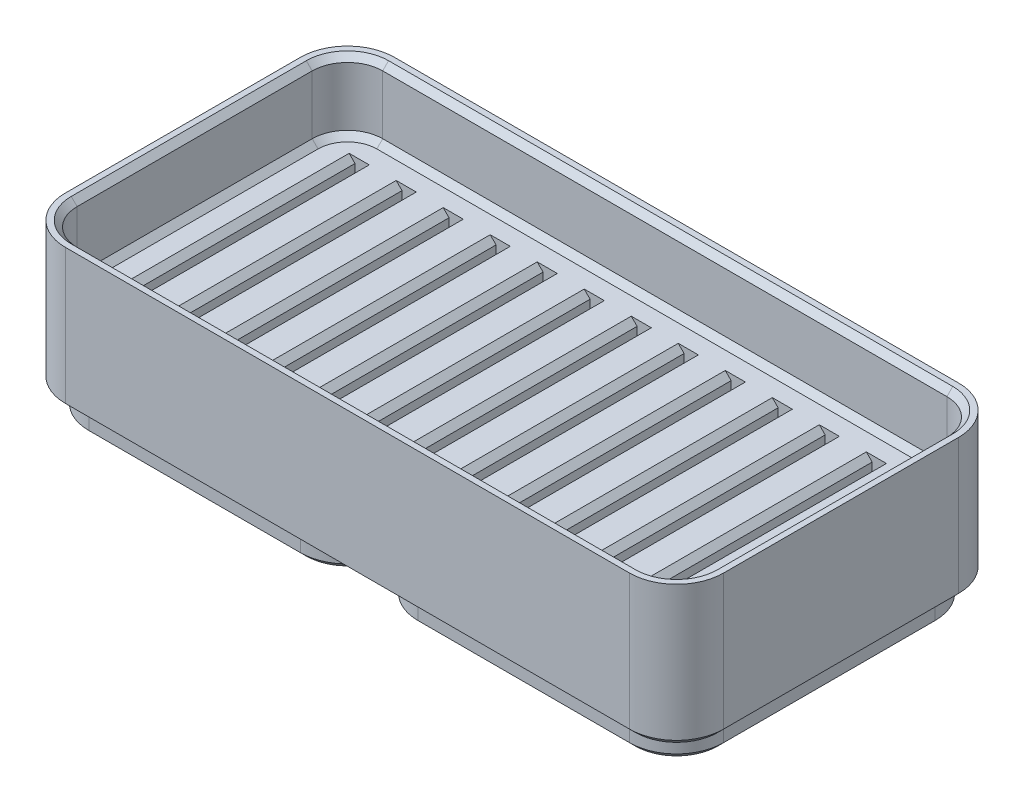
SolidWorks part; units mm, degrees
ref_plane "Front Plane" through (0, 0, 0) normal (0, 0, 1) x (1, 0, 0)
ref_plane "Top Plane" through (0, 0, 0) normal (0, 1, 0) x (1, 0, 0)
ref_plane "Right Plane" through (0, 0, 0) normal (1, 0, 0) x (0, 0, -1)
sketch "Sketch5" plane through (0, 0, 0) normal (0, 1, 0) x (1, 0, 0)
  line L1 (-22.5, -32.5) -> (22.5, -32.5)
  line L2 (-32.5, -22.5) -> (-32.5, 22.5)
  line L3 (-22.5, 32.5) -> (22.5, 32.5)
  line L4 (32.5, -22.5) -> (32.5, 22.5)
  line L5 (-32.5, -32.5) -> (32.5, 32.5) construction
  line L6 (-32.5, 32.5) -> (32.5, -32.5) construction
  arc A0 (-22.5, -32.5) -> (-32.5, -22.5) centre (-22.5, -22.5) cw
  arc A1 (22.5, -32.5) -> (32.5, -22.5) centre (22.5, -22.5) ccw
  arc A2 (22.5, 32.5) -> (32.5, 22.5) centre (22.5, 22.5) cw
  arc A3 (-32.5, 22.5) -> (-22.5, 32.5) centre (-22.5, 22.5) cw
  point P0 (0, 0)
  dimension "D3" = 10
  dimension "D1" = 65
  dimension "D2" = 65
extrude "Boss-Extrude4" add sketch "Sketch5" along normal blind 5
sketch "Sketch6" plane through (0, 5, 0) normal (0, 1, 0) x (1, 0, 0)
  line L1 (35, 35) -> (-35, 35)
  line L2 (35, 35) -> (35, -35)
  line L3 (35, -35) -> (-35, -35)
  line L4 (-35, 35) -> (-35, -35)
  line L5 (35, 35) -> (-35, -35) construction
  line L6 (35, -35) -> (-35, 35) construction
  point P0 (0, 0)
extrude "Boss-Extrude5" add sketch "Sketch6" along normal blind 30
sketch "Sketch8" plane through (0, 0, 0) normal (0, -1, 0) x (1, 0, 0)
  line L0 (-29.5711, 29.5711) -> (-22.5, 22.5)
  arc A0 (-22.5, 32.5) -> (-32.5, 22.5) centre (-22.5, 22.5) ccw construction
  circle A1 centre (-26.0355, 26.0355) radius 3
  circle A2 centre (26.0365, 26.0365) radius 3
  circle A3 centre (26.0375, -26.0355) radius 3
  circle A4 centre (-26.0345, -26.0365) radius 3
  point P8 (0, 0)
  point P15 (0.001, 0.001)
  point P18 (0.002, 0)
  point P21 (0.001, -0.001)
  point P22 (0.001, 0)
  dimension "D1" = 4
extrude "Cut-Extrude1" cut sketch "Sketch8" against normal blind 2 contours A3 | A2 | L0 A1 | L0 A1 | A4
mirror "Mirror1" about plane through (-35, 35, -35) normal (1, 0, 0) of bodies 112
sketch "Sketch9" plane through (0, 35, 0) normal (0, 1, 0) x (1, 0, 0)
  line L8 (32.5, 32.5) -> (-102.5, 32.5)
  line L9 (-102.5, 32.5) -> (-102.5, -32.5)
  line L10 (-102.5, -32.5) -> (32.5, -32.5)
  line L11 (32.5, -32.5) -> (32.5, 32.5)
  line L12 (22.5, 32.5) -> (-92.5, 32.5)
  line L13 (-102.5, 22.5) -> (-102.5, -22.5)
  line L14 (-92.5, -32.5) -> (22.5, -32.5)
  line L15 (32.5, -22.5) -> (32.5, 22.5)
  arc A0 (-102.5, -22.5) -> (-92.5, -32.5) centre (-92.5, -22.5) ccw
  arc A1 (22.5, -32.5) -> (32.5, -22.5) centre (22.5, -22.5) ccw
  arc A2 (22.5, 32.5) -> (32.5, 22.5) centre (22.5, 22.5) cw
  arc A3 (-92.5, 32.5) -> (-102.5, 22.5) centre (-92.5, 22.5) ccw
  dimension "D2" = 10
  dimension "D1" = 2.5
extrude "Cut-Extrude2" cut sketch "Sketch9" against normal blind 30
sketch "Sketch10" plane through (0, 5, 0) normal (0, -1, 0) x (1, 0, 0)
  line L8 (35, 35) -> (-105, 35)
  line L9 (-105, 35) -> (-105, -35)
  line L10 (-105, -35) -> (35, -35)
  line L11 (35, -35) -> (35, 35)
  line L12 (35, 35) -> (-105, 35)
  line L13 (-105, 35) -> (-105, -35)
  line L14 (-105, -35) -> (35, -35)
  line L15 (35, -35) -> (35, 35)
  dimension "D1" = 0
extrude "Boss-Extrude6" add sketch "Sketch10" against normal blind 2.5
fillet "Fillet1" radius 10 4 edges at (35, 20, -35) (35, 20, 35) (-105, 20, 35) (-105, 20, -35)
sketch "Sketch11" plane through (0, 35, 0) normal (0, 1, 0) x (1, 0, 0)
  line L0 (22.5, 32.5) -> (-92.5, 32.5) construction
  line L1 (-136.2871, 123.1679) -> (66.2871, 123.1679)
  line L2 (-136.2871, 123.1679) -> (-136.2871, -58.1679)
  line L3 (-136.2871, -58.1679) -> (66.2871, -58.1679)
  line L4 (66.2871, 123.1679) -> (66.2871, -58.1679)
  line L5 (-136.2871, 123.1679) -> (66.2871, -58.1679) construction
  line L6 (-136.2871, -58.1679) -> (66.2871, 123.1679) construction
  point P0 (-35, 32.5)
extrude "Cut-Extrude3" cut sketch "Sketch11" against normal blind 27.5
sketch "Sketch12" plane through (0, 7.5, 0) normal (0, 1, 0) x (1, 0, 0)
  line L4 (-85.8875, -27.5) -> (-85.8875, 27.5)
  line L5 (-85.8875, -27.5) -> (-84.1125, -27.5)
  line L6 (-84.1125, -27.5) -> (-84.1125, 27.5)
  line L7 (-85.8875, 27.5) -> (-84.1125, 27.5)
  line L12 (-75.8875, -27.5) -> (-75.8875, 27.5)
  line L13 (-75.8875, -27.5) -> (-74.1125, -27.5)
  line L14 (-74.1125, -27.5) -> (-74.1125, 27.5)
  line L15 (-75.8875, 27.5) -> (-74.1125, 27.5)
  line L20 (-65.8875, -27.5) -> (-65.8875, 27.5)
  line L21 (-65.8875, -27.5) -> (-64.1125, -27.5)
  line L22 (-64.1125, -27.5) -> (-64.1125, 27.5)
  line L23 (-65.8875, 27.5) -> (-64.1125, 27.5)
  line L28 (-55.8875, -27.5) -> (-55.8875, 27.5)
  line L29 (-55.8875, -27.5) -> (-54.1125, -27.5)
  line L30 (-54.1125, -27.5) -> (-54.1125, 27.5)
  line L31 (-55.8875, 27.5) -> (-54.1125, 27.5)
  line L36 (-45.8875, -27.5) -> (-45.8875, 27.5)
  line L37 (-45.8875, -27.5) -> (-44.1125, -27.5)
  line L38 (-44.1125, -27.5) -> (-44.1125, 27.5)
  line L39 (-45.8875, 27.5) -> (-44.1125, 27.5)
  line L44 (-35.8875, -27.5) -> (-35.8875, 27.5)
  line L59 (0, 0) -> (-7.2841, 0) construction
  line L60 (-95.8875, -27.5) -> (-94.1125, -27.5)
  line L61 (-95.8875, -27.5) -> (-95.8875, 27.5)
  line L62 (-95.8875, 27.5) -> (-94.1125, 27.5)
  line L63 (-94.1125, -27.5) -> (-94.1125, 27.5)
  line L64 (-95.8875, -27.5) -> (-94.1125, 27.5) construction
  line L65 (-95.8875, 27.5) -> (-94.1125, -27.5) construction
  line L66 (-35.8875, -27.5) -> (-34.1125, -27.5)
  line L67 (-34.1125, -27.5) -> (-34.1125, 27.5)
  line L68 (-35.8875, 27.5) -> (-34.1125, 27.5)
  line L73 (-25.8875, -27.5) -> (-25.8875, 27.5)
  line L74 (-25.8875, -27.5) -> (-24.1125, -27.5)
  line L75 (-24.1125, -27.5) -> (-24.1125, 27.5)
  line L76 (-25.8875, 27.5) -> (-24.1125, 27.5)
  line L81 (-15.8875, -27.5) -> (-15.8875, 27.5)
  line L82 (-15.8875, -27.5) -> (-14.1125, -27.5)
  line L83 (-14.1125, -27.5) -> (-14.1125, 27.5)
  line L84 (-15.8875, 27.5) -> (-14.1125, 27.5)
  line L89 (-5.8875, -27.5) -> (-5.8875, 27.5)
  line L90 (-5.8875, -27.5) -> (-4.1125, -27.5)
  line L91 (-4.1125, -27.5) -> (-4.1125, 27.5)
  line L92 (-5.8875, 27.5) -> (-4.1125, 27.5)
  line L97 (4.1125, -27.5) -> (4.1125, 27.5)
  line L98 (4.1125, -27.5) -> (5.8875, -27.5)
  line L99 (5.8875, -27.5) -> (5.8875, 27.5)
  line L100 (4.1125, 27.5) -> (5.8875, 27.5)
  line L105 (14.1125, -27.5) -> (14.1125, 27.5)
  line L106 (14.1125, -27.5) -> (15.8875, -27.5)
  line L107 (15.8875, -27.5) -> (15.8875, 27.5)
  line L108 (14.1125, 27.5) -> (15.8875, 27.5)
  line L113 (24.1125, -27.5) -> (24.1125, 27.5)
  line L114 (24.1125, -27.5) -> (25.8875, -27.5)
  line L115 (25.8875, -27.5) -> (25.8875, 27.5)
  line L116 (24.1125, 27.5) -> (25.8875, 27.5)
  line L137 (-105, 25) -> (-105, -25)
  line L138 (-95, -35) -> (25, -35)
  line L139 (35, -25) -> (35, 25)
  line L140 (25, 35) -> (-95, 35)
  line L141 (-105, 25) -> (-105, -25)
  line L142 (-95, -35) -> (25, -35)
  line L143 (35, -25) -> (35, 25)
  line L144 (25, 35) -> (-95, 35)
  line L145 (-90.8875, -27.5) -> (-90.8875, 27.5) [skipped]
  line L146 (-90.8875, 27.5) -> (-89.1125, 27.5) [skipped]
  line L147 (-89.1125, -27.5) -> (-89.1125, 27.5) [skipped]
  line L148 (-90.8875, -27.5) -> (-89.1125, -27.5) [skipped]
  line L149 (-80.8875, -27.5) -> (-80.8875, 27.5) [skipped]
  line L150 (-80.8875, 27.5) -> (-79.1125, 27.5) [skipped]
  line L151 (-79.1125, -27.5) -> (-79.1125, 27.5) [skipped]
  line L152 (-80.8875, -27.5) -> (-79.1125, -27.5) [skipped]
  line L153 (-70.8875, -27.5) -> (-70.8875, 27.5) [skipped]
  line L154 (-70.8875, 27.5) -> (-69.1125, 27.5) [skipped]
  line L155 (-69.1125, -27.5) -> (-69.1125, 27.5) [skipped]
  line L156 (-70.8875, -27.5) -> (-69.1125, -27.5) [skipped]
  line L157 (-60.8875, -27.5) -> (-60.8875, 27.5) [skipped]
  line L158 (-60.8875, 27.5) -> (-59.1125, 27.5) [skipped]
  line L159 (-59.1125, -27.5) -> (-59.1125, 27.5) [skipped]
  line L160 (-60.8875, -27.5) -> (-59.1125, -27.5) [skipped]
  line L161 (-50.8875, -27.5) -> (-50.8875, 27.5) [skipped]
  line L162 (-50.8875, 27.5) -> (-49.1125, 27.5) [skipped]
  line L163 (-49.1125, -27.5) -> (-49.1125, 27.5) [skipped]
  line L164 (-50.8875, -27.5) -> (-49.1125, -27.5) [skipped]
  line L165 (-40.8875, -27.5) -> (-40.8875, 27.5) [skipped]
  line L166 (-40.8875, 27.5) -> (-39.1125, 27.5) [skipped]
  line L167 (-39.1125, -27.5) -> (-39.1125, 27.5) [skipped]
  line L168 (-40.8875, -27.5) -> (-39.1125, -27.5) [skipped]
  line L169 (-30.8875, -27.5) -> (-30.8875, 27.5) [skipped]
  line L170 (-30.8875, 27.5) -> (-29.1125, 27.5) [skipped]
  line L171 (-29.1125, -27.5) -> (-29.1125, 27.5) [skipped]
  line L172 (-30.8875, -27.5) -> (-29.1125, -27.5) [skipped]
  line L173 (-20.8875, -27.5) -> (-20.8875, 27.5) [skipped]
  line L174 (-20.8875, 27.5) -> (-19.1125, 27.5) [skipped]
  line L175 (-19.1125, -27.5) -> (-19.1125, 27.5) [skipped]
  line L176 (-20.8875, -27.5) -> (-19.1125, -27.5) [skipped]
  line L177 (-10.8875, -27.5) -> (-10.8875, 27.5) [skipped]
  line L178 (-10.8875, 27.5) -> (-9.1125, 27.5) [skipped]
  line L179 (-9.1125, -27.5) -> (-9.1125, 27.5) [skipped]
  line L180 (-10.8875, -27.5) -> (-9.1125, -27.5) [skipped]
  line L181 (-0.8875, -27.5) -> (-0.8875, 27.5) [skipped]
  line L182 (-0.8875, 27.5) -> (0.8875, 27.5) [skipped]
  line L183 (0.8875, -27.5) -> (0.8875, 27.5) [skipped]
  line L184 (-0.8875, -27.5) -> (0.8875, -27.5) [skipped]
  line L185 (9.1125, -27.5) -> (9.1125, 27.5) [skipped]
  line L186 (9.1125, 27.5) -> (10.8875, 27.5) [skipped]
  line L187 (10.8875, -27.5) -> (10.8875, 27.5) [skipped]
  line L188 (9.1125, -27.5) -> (10.8875, -27.5) [skipped]
  line L189 (20.8875, -27.5) -> (20.8875, 27.5) [skipped]
  line L190 (19.1125, -27.5) -> (19.1125, 27.5) [skipped]
  line L191 (19.1125, 27.5) -> (20.8875, 27.5) [skipped]
  line L192 (19.1125, -27.5) -> (20.8875, -27.5) [skipped]
  arc A24 (-105, -25) -> (-95, -35) centre (-95, -25) ccw
  arc A25 (25, -35) -> (35, -25) centre (25, -25) ccw
  arc A26 (35, 25) -> (25, 35) centre (25, 25) ccw
  arc A27 (-95, 35) -> (-105, 25) centre (-95, 25) ccw
  arc A28 (-105, -25) -> (-95, -35) centre (-95, -25) ccw
  arc A29 (25, -35) -> (35, -25) centre (25, -25) ccw
  arc A30 (35, 25) -> (25, 35) centre (25, 25) ccw
  arc A31 (-95, 35) -> (-105, 25) centre (-95, 25) ccw
  point P0 (-95, 0)
  dimension "D1" = 1.775
  dimension "D2" = 55
  dimension "D4" = 0
  dimension "D3" = 25
extrude "Boss-Extrude9" add sketch "Sketch12" along normal blind 27.5
sketch "Sketch13" plane through (0, 35, 0) normal (0, 1, 0) x (1, 0, 0)
  line L23 (32.5, -25) -> (32.5, 25)
  line L24 (-95, -32.5) -> (25, -32.5)
  line L25 (-102.5, 25) -> (-102.5, -25)
  line L26 (25, 32.5) -> (-95, 32.5)
  line L27 (32.5, -25) -> (32.5, 25)
  line L28 (-95, -32.5) -> (25, -32.5)
  line L29 (-102.5, 25) -> (-102.5, -25)
  line L30 (25, 32.5) -> (-95, 32.5)
  arc A21 (32.5, 25) -> (25, 32.5) centre (25, 25) ccw
  arc A22 (25, -32.5) -> (32.5, -25) centre (25, -25) ccw
  arc A23 (-102.5, -25) -> (-95, -32.5) centre (-95, -25) ccw
  arc A24 (-95, 32.5) -> (-102.5, 25) centre (-95, 25) ccw
  arc A25 (32.5, 25) -> (25, 32.5) centre (25, 25) ccw
  arc A26 (25, -32.5) -> (32.5, -25) centre (25, -25) ccw
  arc A27 (-102.5, -25) -> (-95, -32.5) centre (-95, -25) ccw
  arc A28 (-95, 32.5) -> (-102.5, 25) centre (-95, 25) ccw
  dimension "D1" = 2.5
extrude "Cut-Extrude4" cut sketch "Sketch13" against normal blind 15
chamfer "Chamfer2" distance 1.25 angle 45 16 edges at (-35, 20, 32.5) (30.3033, 20, 30.3033) (-100.3033, 20, 30.3033) (32.5, 20, 0) (-102.5, 20, 0) (30.3033, 20, -30.3033) (-100.3033, 20, -30.3033) (-35, 20, -32.5) (-35, 35, 32.5) (30.3033, 35, 30.3033) (-100.3033, 35, 30.3033) (32.5, 35, 0) (-102.5, 35, 0) (30.3033, 35, -30.3033) (-100.3033, 35, -30.3033) (-35, 35, -32.5)
chamfer "Chamfer4" distance 1.25 angle 45 24 edges at (-35, 5, -35) (-102.0711, 5, -32.0711) (32.0711, 5, -32.0711) (-105, 5, 0) (35, 5, 0) (-102.0711, 5, 32.0711) (32.0711, 5, 32.0711) (-35, 5, 35) (-70, 0, -32.5) (-40.4289, 0, -29.5711) (-99.5711, 0, -29.5711) (-37.5, 0, 0) (-102.5, 0, 0) (-40.4289, 0, 29.5711) (-99.5711, 0, 29.5711) (-70, 0, 32.5) (0, 0, -32.5) (-29.5711, 0, -29.5711) (29.5711, 0, -29.5711) (-32.5, 0, 0) (32.5, 0, 0) (-29.5711, 0, 29.5711) (29.5711, 0, 29.5711) (0, 0, 32.5)
chamfer "Chamfer5" distance 1.25 angle 45 26 edges at (24.1125, 20, 0) (25.8875, 20, 0) (15.8875, 20, 0) (14.1125, 20, 0) (4.1125, 20, 0) (5.8875, 20, 0) (-5.8875, 20, 0) (-4.1125, 20, 0) (-15.8875, 20, 0) (-14.1125, 20, 0) (-24.1125, 20, 0) (-25.8875, 20, 0) (-34.1125, 20, 0) (-35.8875, 20, 0) (-44.1125, 20, 0) (-45.8875, 20, 0) (-54.1125, 20, 0) (-55.8875, 20, 0) (-64.1125, 20, 0) (-65.8875, 20, 0) (-74.1125, 20, 0) (-75.8875, 20, 0) (-84.1125, 20, 0) (-85.8875, 20, 0) (-94.1125, 20, 0) (-95.8875, 20, 0)
